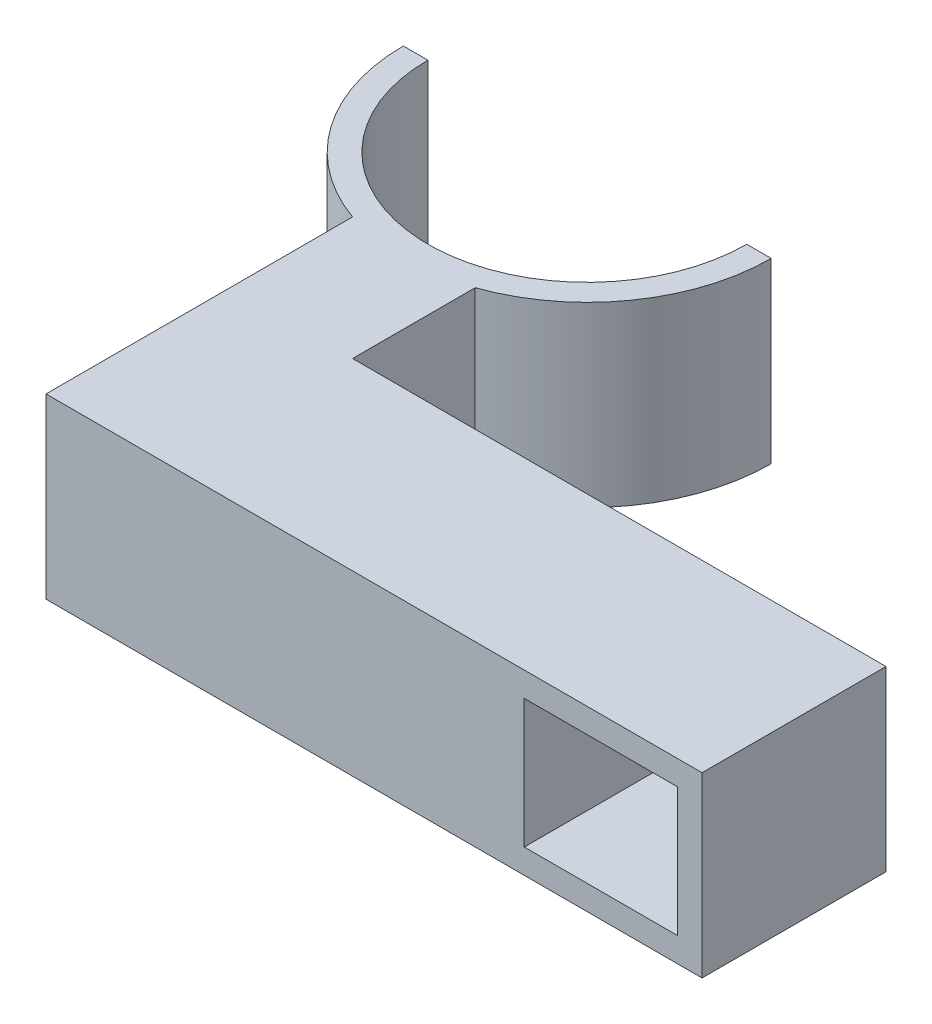
SolidWorks part; units mm, degrees
ref_plane "Front Plane" through (0, 0, 0) normal (0, 0, 1) x (1, 0, 0)
ref_plane "Top Plane" through (0, 0, 0) normal (0, 1, 0) x (1, 0, 0)
ref_plane "Right Plane" through (0, 0, 0) normal (1, 0, 0) x (0, 0, -1)
sketch "Sketch1" plane through (0, 0, 0) normal (0, 0, 1) x (1, 0, 0)
  line L0 (-2, 2) -> (-2, -12.5)
  line L1 (0, 0) -> (12.5, 0)
  line L2 (0, 0) -> (0, -10.5)
  line L3 (0, -10.5) -> (12.5, -10.5)
  line L4 (12.5, 0) -> (12.5, -10.5)
  line L5 (-2, -12.5) -> (14.5, -12.5)
  line L6 (14.5, 2) -> (14.5, -12.5)
  line L7 (-2, 2) -> (14.5, 2)
  dimension "D1" = 12.5
  dimension "D2" = 10.5
  dimension "D3" = 2
extrude "Boss-Extrude1" add sketch "Sketch1" along normal blind 15
sketch "Sketch2" plane through (-2, 0, 0) normal (-1, 0, 0) x (0, 0, 1)
  line L1 (0, 2) -> (15, 2)
  line L2 (0, 2) -> (0, -12.5)
  line L3 (0, -12.5) -> (15, -12.5)
  line L4 (15, 2) -> (15, -12.5)
extrude "Boss-Extrude2" add sketch "Sketch2" along normal blind 37
sketch "Sketch3" plane through (0, 0, 0) normal (0, 0, -1) x (-1, 0, 0)
  line L0 (39, -12.5) -> (-14.5, -12.5) construction
  line L1 (39, 2) -> (29, 2)
  line L2 (39, 2) -> (39, -12.5)
  line L3 (39, -12.5) -> (29, -12.5)
  line L4 (29, 2) -> (29, -12.5)
  dimension "D1" = 10
extrude "Boss-Extrude3" add sketch "Sketch3" along normal blind 10
sketch "Sketch4" plane through (0, 2, 0) normal (0, 1, 0) x (1, 0, 0)
  line L0 (-19, 24.1421) -> (-21, 24.1421)
  line L1 (-47, 24.1421) -> (-49, 24.1421)
  arc A0 (-47, 24.1421) -> (-21, 24.1421) centre (-34, 24.1421) ccw
  arc A1 (-49, 24.1421) -> (-19, 24.1421) centre (-34, 24.1421) ccw
  dimension "D1" = 26
  dimension "D2" = 2
extrude "Boss-Extrude4" add sketch "Sketch4" against normal blind 14.5
